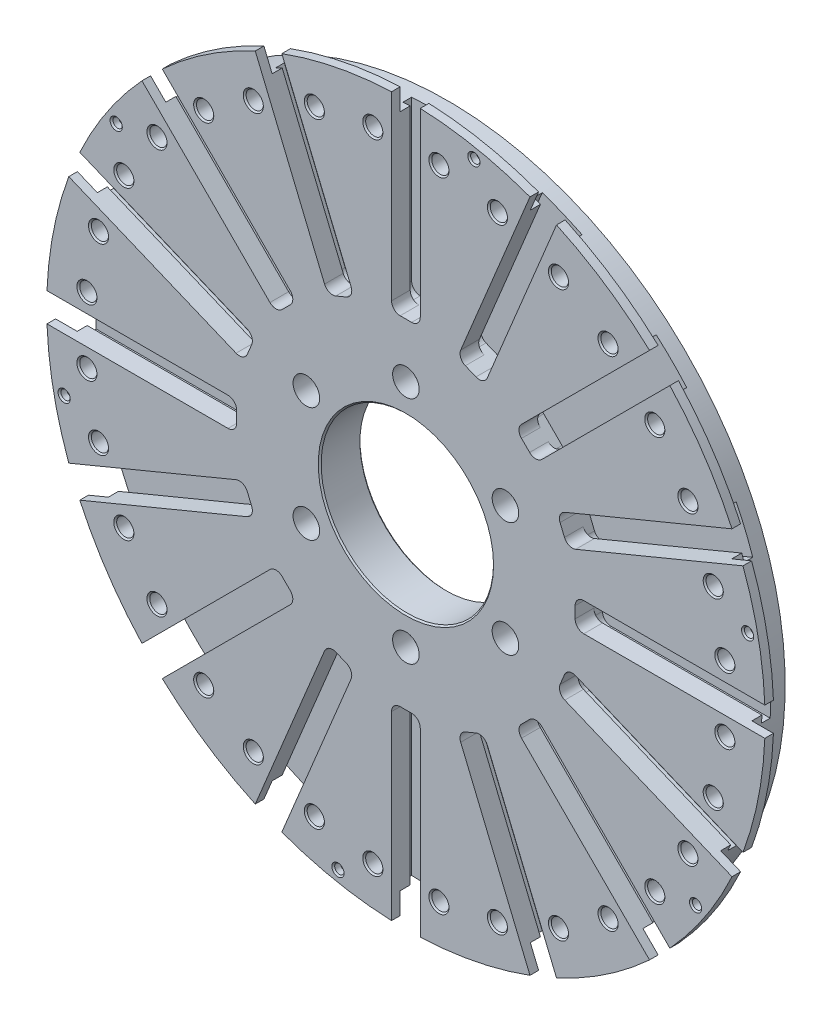
SolidWorks part; units mm, degrees
ref_plane "Piano frontale" through (0, 0, 0) normal (0, 0, 1) x (1, 0, 0)
ref_plane "Piano superiore" through (0, 0, 0) normal (0, 1, 0) x (1, 0, 0)
ref_plane "Piano destro" through (0, 0, 0) normal (1, 0, 0) x (0, 0, -1)
sketch "Schizzo1" plane through (0, 0, 0) normal (0, 0, 1) x (1, 0, 0)
  circle A0 centre (0, 0) radius 250
  dimension "D1" = 500
extrude "Estrusione-Estrusione1" add sketch "Schizzo1" against normal blind 29
sketch "Schizzo2" plane through (0, 0, -29) normal (0, 0, -1) x (-1, 0, 0)
  circle A0 centre (0, 0) radius 250
  circle A1 centre (0, 0) radius 235
  dimension "D1" = 500
  dimension "D2" = 470
extrude "Taglio-Estrusione1" cut sketch "Schizzo2" against normal blind 23
hole_wizard "Foro1" positions "Schizzo5" profile "Schizzo4" legacy
sketch "Schizzo5" plane through (0, 0, 0) normal (0, 0, 1) x (1, 0, 0)
  point P0 (0, 80)
  dimension "D1" = 80
sketch "Schizzo4" plane through (0, 80, 0) normal (1, 0, 0) x (0, -1, 0)
  line L0 (0, 0) -> (0, 29.8496)
  line L1 (0, 29.8496) -> (6.25, 29.8496)
  line L2 (6.25, 29.8496) -> (6.25, 13)
  line L3 (6.25, 13) -> (9.25, 13)
  line L4 (9.25, 13) -> (9.25, 0)
  line L5 (9.25, 0) -> (0, 0)
  line L6 (0, 110) -> (0, -10) construction
  dimension "Diameter" = 12.5
  dimension "Depth" = 30
  dimension "C-Bore Diameter" = 18.5
  dimension "C-Bore Depth" = 13
pattern_circular "RipetizioneCircolare1" count 6 every 60 about axis through (0, 0, 0) along (0, 0, 1) of "Foro1"
hole_wizard "Foro Ø12.0 (12)-1" positions "Schizzo6" profile "Schizzo7" hole size "Ø12.0" standard "ISO"
sketch "Schizzo6" plane through (0, 0, 0) normal (0, 0, 1) x (1, 0, 0)
  point P0 (-222, 23)
  dimension "D1" = 222
  dimension "D2" = 23
sketch "Schizzo7" plane through (-222, 23, 0) normal (1, 0, 0) x (0, -1, 0)
  line L0 (0, 0) -> (0, 32.6042)
  line L1 (0, 32.6042) -> (6, 28.999)
  line L2 (6, 28.999) -> (6, 0)
  line L5 (6, 0) -> (0, 0)
  line L10 (0, 32.6042) -> (-6, 28.999) construction
  line L11 (0, -6.35) -> (0, 107.95) construction
  dimension "Hole Dia." = 12
  dimension "Hole Depth" = 28.999
  dimension "Drill Angle" = 118
sketch "Schizzo9" plane through (0, 0, 0) normal (0, 0, 1) x (1, 0, 0)
  circle A0 centre (0, 0) radius 60
  dimension "D1" = 120
extrude "Taglio-Estrusione2" cut sketch "Schizzo9" against normal up to surface (29 mm away) up to face at (75.532, 40, -29)
mirror "Specchia1" about plane through (0, 0, 0) normal (0, 1, 0) of "Foro Ø12.0 (12)-1"
sketch "Schizzo10" plane through (0, 0, 0) normal (0, 0, 1) x (1, 0, 0)
  circle A1 centre (-201.6314, 134.7258) radius 3.25
  dimension "D2" = 6.5
extrude "Taglio-Estrusione3" cut sketch "Schizzo10" against normal up to surface (6 mm away) up to face at (-235, 0, -6)
pattern_circular "RipetizioneCircolare3" count 3 every 67.5 about axis through (0, 0, 0) along (0, 0, 1) of "Taglio-Estrusione3"
sketch "Schizzo11" plane through (0, 0, 0) normal (0, 0, 1) x (1, 0, 0)
  circle A0 centre (-237.8404, -47.3094) radius 3.25
  dimension "D1" = 6.5
  dimension "D2" = 242.5
  dimension "D3" = 47.3094
extrude "Taglio-Estrusione4" cut sketch "Schizzo11" against normal up to surface (6 mm away) up to face at (44.0594, 237.8404, -6)
pattern_circular "RipetizioneCircolare4" count 3 every 67.5 about axis through (0, 0, 0) along (0, 0, 1) of "Taglio-Estrusione4"
sketch "Schizzo13" plane through (0, 0, 0) normal (0, 0, 1) x (1, 0, 0)
  line L0 (-277.7976, 0) -> (264.694, 0) construction
  line L1 (-117.7999, 4) -> (-117.7999, -4)
  line L2 (-123.7999, -10) -> (-249.7999, -10)
  line L3 (-123.7999, 10) -> (-249.7999, 10)
  circle A0 centre (0, 0) radius 250 construction
  arc A1 (-249.7999, -10) -> (-249.7999, 10) centre (0, 0) cw
  arc A2 (-117.7999, -4) -> (-123.7999, -10) centre (-123.7999, -4) cw
  arc A3 (-117.7999, 4) -> (-123.7999, 10) centre (-123.7999, 4) ccw
  point P5 (-117.7999, 0)
  point P14 (-117.7999, -10)
  point P17 (-117.7999, 10)
  dimension "D3" = 6
  dimension "D1" = 20
  dimension "D2" = 132
extrude "Taglio-Estrusione5" cut sketch "Schizzo13" against normal blind 13 contours A1 L0 L1 L3 | L0 A1 L2 L1
sketch "Schizzo14" plane through (0, 0, -13) normal (0, 0, 1) x (1, 0, 0)
  line L0 (-117.7999, 4) -> (-117.7999, -4) construction
  line L1 (-117.7999, 9) -> (-117.7999, -9)
  line L2 (-123.7999, -15) -> (-235, -15)
  line L3 (-235, -15) -> (-235, 15)
  line L4 (-235, 15) -> (-123.7999, 15)
  line L5 (0, 0) -> (-267.0393, 0) construction
  arc A0 (-234.7871, 10) -> (-234.7871, -10) centre (0, 0) ccw construction
  arc A1 (-117.7999, -9) -> (-123.7999, -15) centre (-123.7999, -9) cw
  arc A2 (-117.7999, 9) -> (-123.7999, 15) centre (-123.7999, 9) ccw
  point P7 (-117.7999, 0)
  point P8 (-235, 0)
  point P16 (-117.7999, -15)
  point P19 (-117.7999, 15)
  dimension "D2" = 6
  dimension "D1" = 30
extrude "Taglio-Estrusione6" cut sketch "Schizzo14" against normal blind 6
chamfer "Smusso1" distance 1 angle 45 2 edges at (60, 0, -29) (60, 0, 0)
pattern_circular "RipetizioneCircolare7" count 16 every 22.5 about axis through (0, 0, 0) along (0, 0, 1) of "Taglio-Estrusione5", "Taglio-Estrusione6", "Foro Ø12.0 (12)-1", "Specchia1"
chamfer "Smusso3" distance 1 angle 45 75 edges at (-216, -23, -29) (-216, -23, 0) (-216, 23, -29) (-216, 23, 0) (219.903, -63.7065, -29) (228, -23, -29) (202.2995, -106.205, -29) (179.2412, -140.7142, -29) (146.7142, -173.2412, -29) (112.205, -196.2995, -29) (69.7065, -213.903, -29) (29, -222, -29) (-17, -222, -29) (-57.7065, -213.903, -29) (-100.205, -196.2995, -29) (-134.7142, -173.2412, -29) (-167.2412, -140.7142, -29) (228, 23, -29) (219.903, 63.7065, -29) (202.2995, 106.205, -29) (179.2412, 140.7142, -29) (146.7142, 173.2412, -29) (112.205, 196.2995, -29) (69.7065, 213.903, -29) (-17, 222, -29) (29, 222, -29) (-57.7065, 213.903, -29) (-100.205, 196.2995, -29) (-134.7142, 173.2412, -29) (-167.2412, 140.7142, -29) (-190.2995, 106.205, -29) (-207.903, 63.7065, -29) (-190.2995, -106.205, -29) (-207.903, -63.7065, -29) (-241.0904, -47.3094, -6) (-50.5594, -237.8404, -6) (234.5904, 47.3094, -6) (44.0594, 237.8404, -6) (-204.8814, 134.7258, -6) (-198.3814, 134.7258, 0) (48.5531, 234.8378, 0) (235.5423, 45.0113, 0) (199.3333, -132.4277, 0) (-46.0657, -234.8378, 0) (-234.5904, -47.3094, 0) (-207.903, -63.7065, 0) (-190.2995, -106.205, 0) (-167.2412, -140.7142, 0) (-134.7142, -173.2412, 0) (-100.205, -196.2995, 0) (-57.7065, -213.903, 0) (-17, -222, 0) (29, -222, 0) (69.7065, -213.903, 0) (112.205, -196.2995, 0) (146.7142, -173.2412, 0) (179.2412, -140.7142, 0) (202.2995, -106.205, 0) (219.903, -63.7065, 0) (228, -23, 0) (228, 23, 0) (219.903, 63.7065, 0) (202.2995, 106.205, 0) (179.2412, 140.7142, 0) (146.7142, 173.2412, 0) (112.205, 196.2995, 0) (69.7065, 213.903, 0) (29, 222, 0) (-17, 222, 0) (-57.7065, 213.903, 0) (-100.205, 196.2995, 0) (-134.7142, 173.2412, 0) (-167.2412, 140.7142, 0) (-190.2995, 106.205, 0) (-207.903, 63.7065, 0)
chamfer "Smusso4" distance 1 angle 45 6 edges at (75.532, 40, -29) (75.532, -40, -29) (6.25, -80, -29) (-63.032, -40, -29) (-63.032, 40, -29) (6.25, 80, -29)
